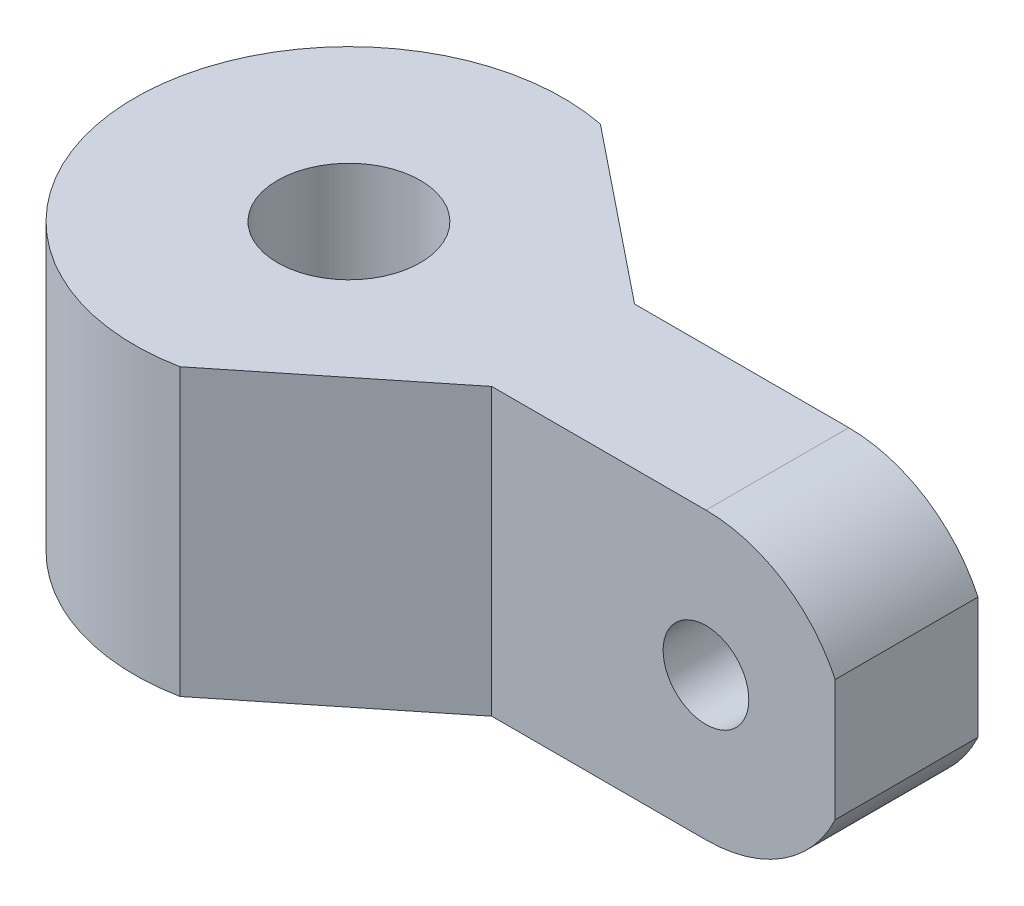
SolidWorks part; units mm, degrees
ref_plane "Alzado" through (0, 0, 0) normal (0, 0, 1) x (1, 0, 0)
ref_plane "Planta" through (0, 0, 0) normal (0, 1, 0) x (1, 0, 0)
ref_plane "Vista lateral" through (0, 0, 0) normal (1, 0, 0) x (0, 0, -1)
sketch "Croquis1" plane through (0, 0, 0) normal (0, 0, 1) x (1, 0, 0)
  line L1 (5, -5) -> (-20, -5)
  line L2 (5, -5) -> (5, 5)
  line L3 (5, 5) -> (-20, 5)
  line L4 (-20, -5) -> (-20, 5)
  circle A0 centre (0, 0) radius 1.5
  dimension "D2" = 3
  dimension "D1" = 25
  dimension "D3" = 10
  dimension "D4" = 5
  dimension "D5" = 5
extrude "Saliente-Extruir1" add sketch "Croquis1" along normal blind 10
sketch "Croquis2" plane through (0, 5, 0) normal (0, 1, 0) x (1, 0, 0)
  line L0 (-20, -10) -> (-20, 0) construction
  line L1 (5, 0) -> (-20, 0) construction
  circle A0 centre (-15, -5) radius 2.5
  dimension "D3" = 5
  dimension "D1" = 5
  dimension "D2" = 5
extrude "Cortar-Extruir1" cut sketch "Croquis2" against normal blind 14
sketch "Croquis3" plane through (5, 0, 0) normal (1, 0, 0) x (0, 0, -1)
  line L0 (-10, -5) -> (0, -5) construction
  line L1 (-7.5, -5) -> (-2.5, -5)
  line L2 (-7.5, -5) -> (-7.5, 5)
  line L3 (-7.5, 5) -> (-2.5, 5)
  line L4 (-2.5, -5) -> (-2.5, 5)
  line L5 (-10, -5) -> (-10, 5) construction
  line L6 (0, -5) -> (0, 5) construction
  dimension "D1" = 2.5
  dimension "D2" = 2.5
  dimension "D3" = 10
extrude "Cortar-Extruir2" cut sketch "Croquis3" against normal blind 12.5 flip side to cut
sketch "Sketch1" plane through (0, 0, 10) normal (0, 0, 1) x (1, 0, 0)
  line L0 (0, 5) -> (0, -7.1106) construction
  line L1 (0, 5) -> (5.9929, 5)
  line L2 (5.9929, 5) -> (5.9929, -6.7488)
  line L3 (5.9929, -6.7488) -> (0, -5)
  line L4 (4.5251, 2.1269) -> (4.5251, -2.1269)
  arc A0 (0, -5) -> (4.5251, -2.1269) centre (0, 0) ccw
  arc A1 (4.5251, 2.1269) -> (0, 5) centre (0, 0) ccw
  dimension "D1" = 4.5251
extrude "Cut-Extrude1" cut sketch "Sketch1" against normal blind 10
sketch "Croquis5" plane through (0, 5, 0) normal (0, 1, 0) x (1, 0, 0)
  line L0 (-12.1154, 1.9231) -> (-7.5, 0)
  line L1 (-7.5, 0) -> (-7.5, -10)
  line L2 (-7.5, -10) -> (-11.5742, -11.6719)
  arc A0 (-12.1154, 1.9231) -> (-11.5742, -11.6719) centre (-15, -5) ccw
  circle A1 centre (-15, -5) radius 2.5
extrude "Saliente-Extruir5" add sketch "Croquis5" against normal blind 10
sketch "Croquis6" plane through (0, 5, 0) normal (0, 1, 0) x (1, 0, 0)
  line L0 (-13.5561, 2.3597) -> (-7.5, -2.5)
  line L1 (-7.5, -2.5) -> (-7.5, 2.3597)
  line L2 (-7.5, 2.3597) -> (-13.5561, 2.3597)
  line L3 (-15, -5) -> (-5.3894, -5) construction
  line L4 (-7.5, -7.5) -> (-7.5, -12.3597)
  line L5 (-7.5, -12.3597) -> (-13.5561, -12.3597)
  line L6 (-13.5561, -12.3597) -> (-7.5, -7.5)
  arc A0 (-12.1154, 1.9231) -> (-11.5742, -11.6719) centre (-15, -5) ccw construction
extrude "Cortar-Extruir3" cut sketch "Croquis6" against normal through all
